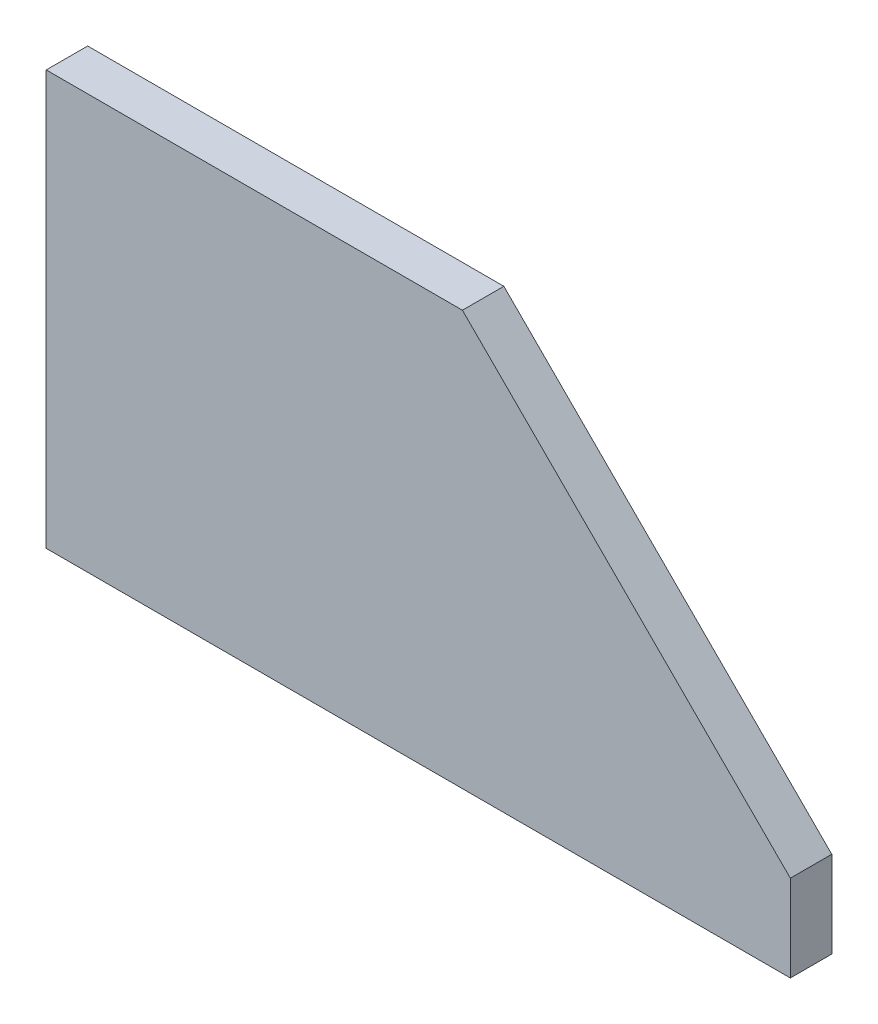
SolidWorks part; units mm, degrees
ref_plane "Front Plane" through (0, 0, 0) normal (0, 0, 1) x (1, 0, 0)
ref_plane "Top Plane" through (0, 0, 0) normal (0, 1, 0) x (1, 0, 0)
ref_plane "Right Plane" through (0, 0, 0) normal (1, 0, 0) x (0, 0, -1)
sketch "Sketch1" plane through (0, 0, 0) normal (0, 0, 1) x (1, 0, 0)
  line L0 (120.53, 120) -> (215.5, 25.03)
  line L1 (0, 0) -> (215.5, 0)
  line L2 (0, 0) -> (0, 120)
  line L3 (0, 120) -> (120.53, 120)
  line L4 (215.5, 0) -> (215.5, 25.03)
  dimension "Width" = 120
  dimension "Length" = 215.5
  dimension "D3" = 120.53
  dimension "D4" = 135
extrude "Extrude1" add sketch "Sketch1" along normal blind 12
